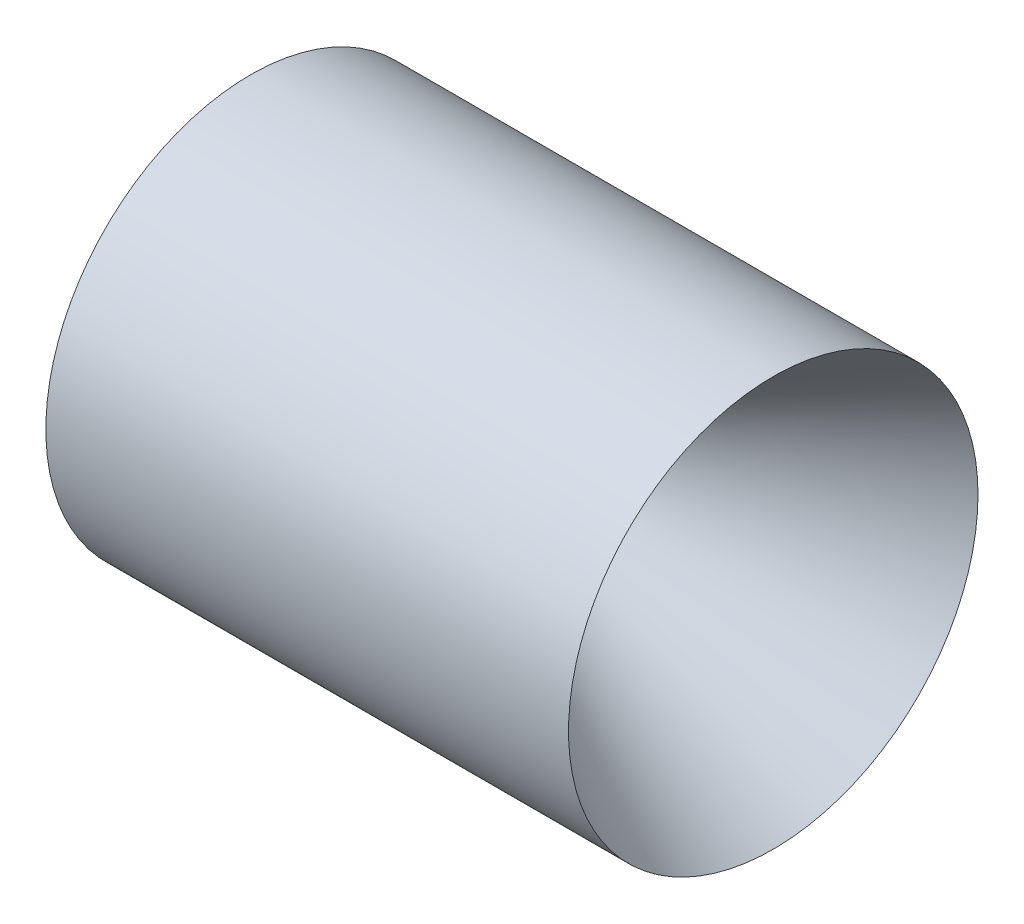
SolidWorks part; units mm, degrees
material "C (Graphite)"
ref_plane "Front Plane" through (0, 0, 0) normal (0, 0, 1) x (1, 0, 0)
ref_plane "Top Plane" through (0, 0, 0) normal (0, 1, 0) x (1, 0, 0)
ref_plane "Right Plane" through (0, 0, 0) normal (1, 0, 0) x (0, 0, -1)
sketch "Sketch1" plane through (0, 0, 0) normal (0, 0, 1) x (1, 0, 0)
  line L0 (11.2724, 0) -> (-90.9907, 0) construction
  line L7 (-85.9728, 17.5) -> (-41.2964, 17.5)
  line L16 (-63.7201, 5) -> (-85.9728, 10.9626)
  line L17 (-85.9728, 10.9626) -> (-85.9728, 17.5)
  line L18 (-62.947, 5) -> (-63.7201, 5)
  line L20 (-41.2964, 17.5) -> (-62.947, 5)
  dimension "D2" = 30
  dimension "D3" = 17.5
  dimension "D1" = 5
  dimension "D4" = 15
revolve "Revolve1" add sketch "Sketch1" angle 360 about L0
